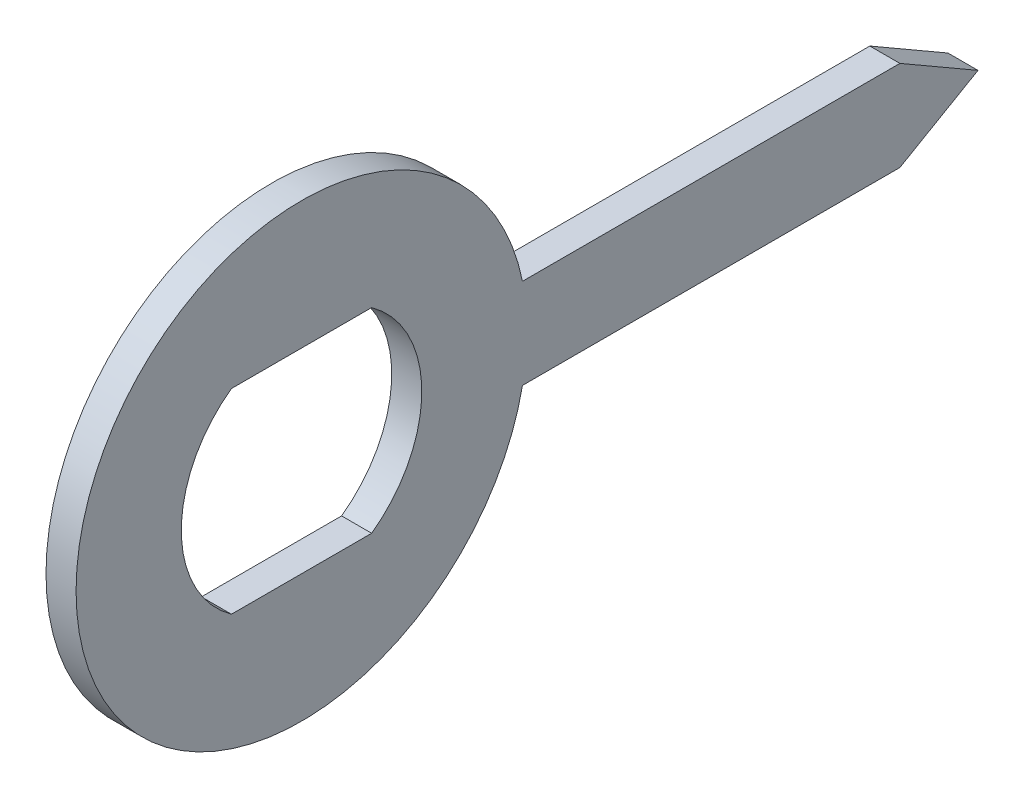
SolidWorks part; units mm, degrees
ref_plane "Face" through (0, 0, 0) normal (0, 0, 1) x (1, 0, 0)
ref_plane "Dessus" through (0, 0, 0) normal (0, 1, 0) x (1, 0, 0)
ref_plane "Droite" through (0, 0, 0) normal (1, 0, 0) x (0, 0, -1)
sketch "Esquisse1" plane through (0, 0, 0) normal (1, 0, 0) x (0, 0, -1)
  line L0 (-4.6637, -6.5) -> (4.6637, -6.5)
  line L1 (14.6969, 3) -> (39.8038, 3)
  line L2 (0, 0) -> (45, 0) construction
  line L3 (14.6969, -3) -> (39.8038, -3)
  line L4 (45, 0) -> (39.8038, -3)
  line L5 (-4.6637, 6.5) -> (4.6637, 6.5)
  line L6 (45, 0) -> (39.8038, 3)
  arc A0 (-4.6637, 6.5) -> (-4.6637, -6.5) centre (0, 0) ccw
  arc A1 (14.6969, 3) -> (14.6969, -3) centre (0, 0) ccw
  arc A5 (4.6637, -6.5) -> (4.6637, 6.5) centre (0, 0) ccw
  dimension "D1" = 3
  dimension "D5" = 30
  dimension "D6" = 16
  dimension "D2" = 3
  dimension "D3" = 45
  dimension "D4" = 30
  dimension "D7" = 6.5
  dimension "D8" = 6.5
extrude "Boss.-Extru.1" add sketch "Esquisse1" along normal blind 2
